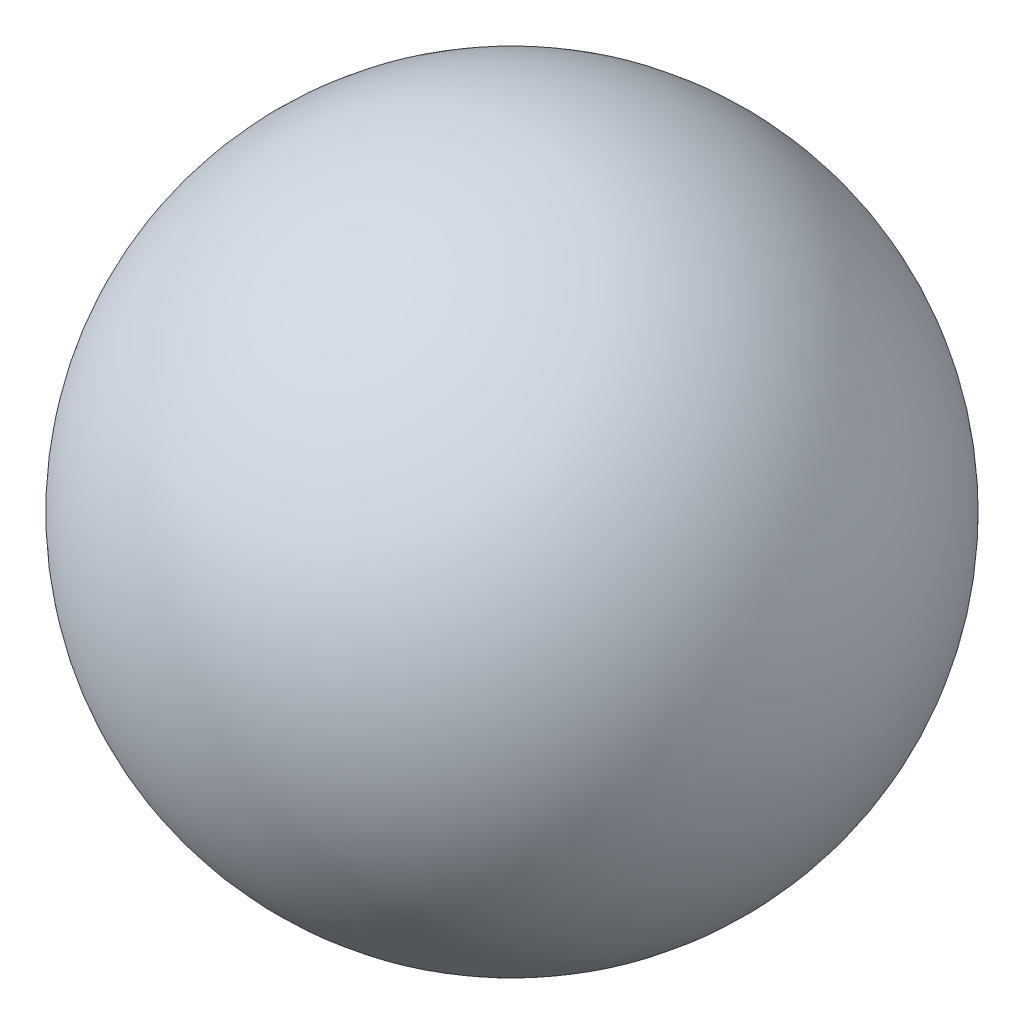
SolidWorks part; units mm, degrees
ref_plane "Front" through (0, 0, 0) normal (0, 0, 1) x (1, 0, 0)
ref_plane "Top" through (0, 0, 0) normal (0, 1, 0) x (1, 0, 0)
ref_plane "Right" through (0, 0, 0) normal (1, 0, 0) x (0, 0, -1)
sketch "Sketch1" plane through (0, 0, 0) normal (0, 0, 1) x (1, 0, 0)
  line L0 (0, -8.1) -> (0, 8.1)
  arc A0 (0, 8.1) -> (0, -8.1) centre (0, 0) cw
  dimension "D1" = 8.1
revolve "Revolve1" add sketch "Sketch1" angle 360 about L0
